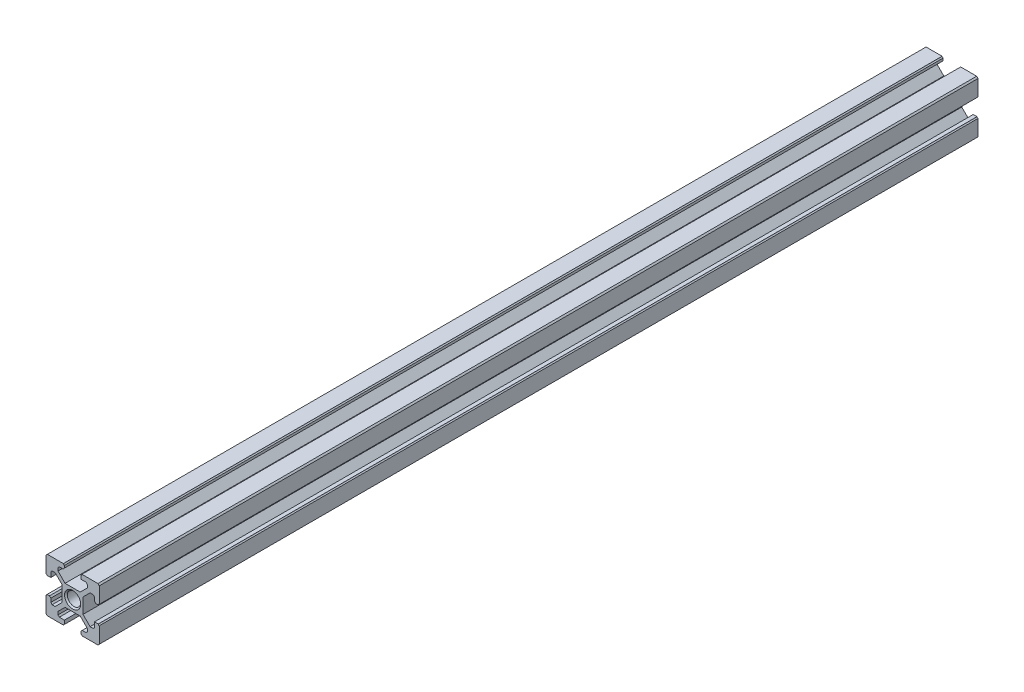
SolidWorks part; units mm, degrees
ref_plane "Front Plane" through (0, 0, 0) normal (0, 0, 1) x (1, 0, 0)
ref_plane "Top Plane" through (0, 0, 0) normal (0, 1, 0) x (1, 0, 0)
ref_plane "Right Plane" through (0, 0, 0) normal (1, 0, 0) x (0, 0, -1)
sketch "Sketch1" plane through (0, 0, 0) normal (0, 0, 1) x (1, 0, 0)
  line L0 (0, 10.7337) -> (0, 0.7337) construction
  line L1 (-9.5, 10) -> (-3.4865, 10)
  line L2 (-10, 9.5) -> (-10, 3.4865)
  line L3 (-9.5, -10) -> (-3.4865, -10)
  line L4 (10, 9.5) -> (10, 3.4865)
  line L5 (-9.75, 9.75) -> (9.75, -9.75) construction
  line L6 (-9.75, -9.75) -> (10, 10) construction
  line L7 (0, 0) -> (-10, 0) construction
  line L8 (3.1, 9.6135) -> (3.1, 8.2)
  line L9 (3.1, 8.2) -> (5, 8.2)
  line L10 (5.5, 7.7) -> (5.5, 6.5607)
  line L11 (5.5, 6.5607) -> (2.8393, 3.9)
  line L12 (2.8393, 3.9) -> (0, 3.9)
  line L13 (3.9, 2.8393) -> (3.9, 0)
  line L14 (6.5607, 5.5) -> (3.9, 2.8393)
  line L15 (9.6135, 3.1) -> (8.7, 3.1)
  line L16 (8.2, 3.6) -> (8.2, 5)
  line L17 (7.7, 5.5) -> (6.5607, 5.5)
  line L18 (3.4865, 10) -> (9.5, 10)
  line L19 (10, -3.4865) -> (10, -9.5)
  line L20 (5, 8.2) -> (5.5, 7.7)
  line L21 (8.2, 5) -> (7.7, 5.5)
  line L22 (9.5, 10) -> (10, 9.5)
  line L23 (8.7, 3.1) -> (8.2, 3.6)
  line L24 (3.9, -2.8393) -> (3.9, 0)
  line L25 (6.5607, -5.5) -> (3.9, -2.8393)
  line L26 (7.7, -5.5) -> (6.5607, -5.5)
  line L27 (8.2, -5) -> (7.7, -5.5)
  line L28 (8.2, -3.1) -> (8.2, -5)
  line L29 (9.6135, -3.1) -> (8.2, -3.1)
  line L30 (10, -3.4865) -> (10, -9.5)
  line L31 (10, -9.5) -> (9.5, -10)
  line L32 (9.5, -10) -> (3.4865, -10)
  line L33 (3.1, -9.6135) -> (3.1, -8.7)
  line L34 (3.1, -8.7) -> (3.6, -8.2)
  line L35 (3.6, -8.2) -> (5, -8.2)
  line L36 (5, -8.2) -> (5.5, -7.7)
  line L37 (5.5, -7.7) -> (5.5, -6.5607)
  line L38 (5.5, -6.5607) -> (2.8393, -3.9)
  line L39 (2.8393, -3.9) -> (0, -3.9)
  line L40 (-2.8393, -3.9) -> (0, -3.9)
  line L41 (-5.5, -6.5607) -> (-2.8393, -3.9)
  line L42 (-5.5, -7.7) -> (-5.5, -6.5607)
  line L43 (-5, -8.2) -> (-5.5, -7.7)
  line L44 (-3.1, -8.2) -> (-5, -8.2)
  line L45 (-3.1, -9.6135) -> (-3.1, -8.2)
  line L46 (-3.4865, -10) -> (-9.5, -10)
  line L47 (-9.5, -10) -> (-10, -9.5)
  line L48 (-10, -9.5) -> (-10, -3.4865)
  line L49 (-9.6135, -3.1) -> (-8.7, -3.1)
  line L50 (-8.7, -3.1) -> (-8.2, -3.6)
  line L51 (-8.2, -3.6) -> (-8.2, -5)
  line L52 (-8.2, -5) -> (-7.7, -5.5)
  line L53 (-7.7, -5.5) -> (-6.5607, -5.5)
  line L54 (-6.5607, -5.5) -> (-3.9, -2.8393)
  line L55 (-3.9, -2.8393) -> (-3.9, 0)
  line L56 (-3.9, 2.8393) -> (-3.9, 0)
  line L57 (-6.5607, 5.5) -> (-3.9, 2.8393)
  line L58 (-7.7, 5.5) -> (-6.5607, 5.5)
  line L59 (-8.2, 5) -> (-7.7, 5.5)
  line L60 (-8.2, 3.1) -> (-8.2, 5)
  line L61 (-9.6135, 3.1) -> (-8.2, 3.1)
  line L62 (-10, 3.4865) -> (-10, 9.5)
  line L63 (-10, 9.5) -> (-9.5, 10)
  line L64 (-9.5, 10) -> (-3.4865, 10)
  line L65 (-3.1, 9.6135) -> (-3.1, 8.7)
  line L66 (-3.1, 8.7) -> (-3.6, 8.2)
  line L67 (-3.6, 8.2) -> (-5, 8.2)
  line L68 (-5, 8.2) -> (-5.5, 7.7)
  line L69 (-5.5, 7.7) -> (-5.5, 6.5607)
  line L70 (-5.5, 6.5607) -> (-2.8393, 3.9)
  line L71 (-2.8393, 3.9) -> (0, 3.9)
  line L72 (3.4865, -10) -> (9.5, -10)
  line L73 (-10, -3.4865) -> (-10, -9.5)
  arc A0 (3.1, 9.6135) -> (3.4865, 10) centre (3.1, 10) ccw
  arc A1 (9.6135, 3.1) -> (10, 3.4865) centre (10, 3.1) cw
  arc A2 (9.6135, -3.1) -> (10, -3.4865) centre (10, -3.1) ccw
  arc A3 (3.1, -9.6135) -> (3.4865, -10) centre (3.1, -10) cw
  arc A4 (-3.1, -9.6135) -> (-3.4865, -10) centre (-3.1, -10) ccw
  arc A5 (-9.6135, -3.1) -> (-10, -3.4865) centre (-10, -3.1) cw
  arc A6 (-9.6135, 3.1) -> (-10, 3.4865) centre (-10, 3.1) ccw
  arc A7 (-3.1, 9.6135) -> (-3.4865, 10) centre (-3.1, 10) cw
  point P0 (0, 0)
  point P13 (5.5, 8.2)
  point P17 (3.1, 8.9068)
  point P22 (8.2, 3.1)
  point P23 (8.2, 5.5)
  point P103 (0, 0)
  dimension "D3" = 1.8
  dimension "D4" = 6.1
  dimension "D5" = 11
  dimension "D6" = 6.2
  dimension "D7" = 1.5
extrude "Boss-Extrude1" add sketch "Sketch1" along normal blind 330 contours L65 A7 L1 L63 L2 A6 L61 L60 L59 L58 L57 L56 L55 L54 L53 L52 L51 L50 L49 A5 L48 L47 L3 A4 L45 L44 L43 L42 L41 L40 L39 L38 L37 L36 L35 L34 L33 A3 L32 L31 L19 A2 L29 L28 L27 L26 L25 L24 L13 L14 L17
hole_wizard "M6x1.0 Tapped Hole1" positions "3DSketch1" profile "Sketch2" tap size "M6x1.0" standard "ANSI Metric"
sketch3d "3DSketch1"
  line L0 (3.9, -2.8393, 330) -> (3.9, 2.8393, 330) construction
  line L1 (2.8393, 3.9, 330) -> (-2.8393, 3.9, 330) construction
  point P0 (0, 0, 0)
  point P3 (0, 0, 0)
  point P5 (0, 0, 0)
  point P7 (0.9996, -8.1302, 0)
  point P9 (0, 0, 0)
  point P11 (0, 0, 330)
  dimension "D1" = 3.9
  dimension "D2" = 3.9
sketch "Sketch2" plane through (0, 0, 330) normal (1, 0, 0) x (0, -1, 0)
  line L0 (0, 0) -> (0, 30)
  line L1 (0, 30) -> (2.5, 28.4978)
  line L2 (2.5, 28.4978) -> (2.5, 0.525)
  line L3 (2.5, 0.525) -> (3.025, 0)
  line L5 (3.025, 0) -> (0, 0)
  line L6 (-2.5, 0.525) -> (-3.025, 0) construction
  line L10 (0, 30) -> (-2.5, 28.4978) construction
  line L11 (0, -6.35) -> (0, 107.95) construction
  dimension "Tap Drill Dia." = 5
  dimension "Tap Drill Depth" = 30
  dimension "Near C'Sink Dia." = 6.05
  dimension "Near C'Sink Angle" = 90
  dimension "Drill Angle" = 118
cosmetic thread "Hole Thread6" parameters "D1"=12, "D2"=6
hole_wizard "M6x1.0 Tapped Hole2" positions "3DSketch2" profile "Sketch3" tap size "M6x1.0" standard "ANSI Metric"
sketch3d "3DSketch2"
  line L0 (2.8393, 3.9, 0) -> (-2.8393, 3.9, 0) construction
  line L1 (3.9, -2.8393, 0) -> (3.9, 2.8393, 0) construction
  point P3 (0, 0, 0)
  dimension "D1" = 3.9
  dimension "D2" = 3.9
sketch "Sketch3" plane through (0, 0, 0) normal (1, 0, 0) x (0, 1, 0)
  line L0 (0, 0) -> (0, 30)
  line L1 (0, 30) -> (2.5, 28.4978)
  line L2 (2.5, 28.4978) -> (2.5, 0.525)
  line L3 (2.5, 0.525) -> (3.025, 0)
  line L5 (3.025, 0) -> (0, 0)
  line L6 (-2.5, 0.525) -> (-3.025, 0) construction
  line L10 (0, 30) -> (-2.5, 28.4978) construction
  line L11 (0, -6.35) -> (0, 107.95) construction
  dimension "Tap Drill Dia." = 5
  dimension "Tap Drill Depth" = 30
  dimension "Near C'Sink Dia." = 6.05
  dimension "Near C'Sink Angle" = 90
  dimension "Drill Angle" = 118
cosmetic thread "Hole Thread7" parameters "D1"=12, "D2"=6
